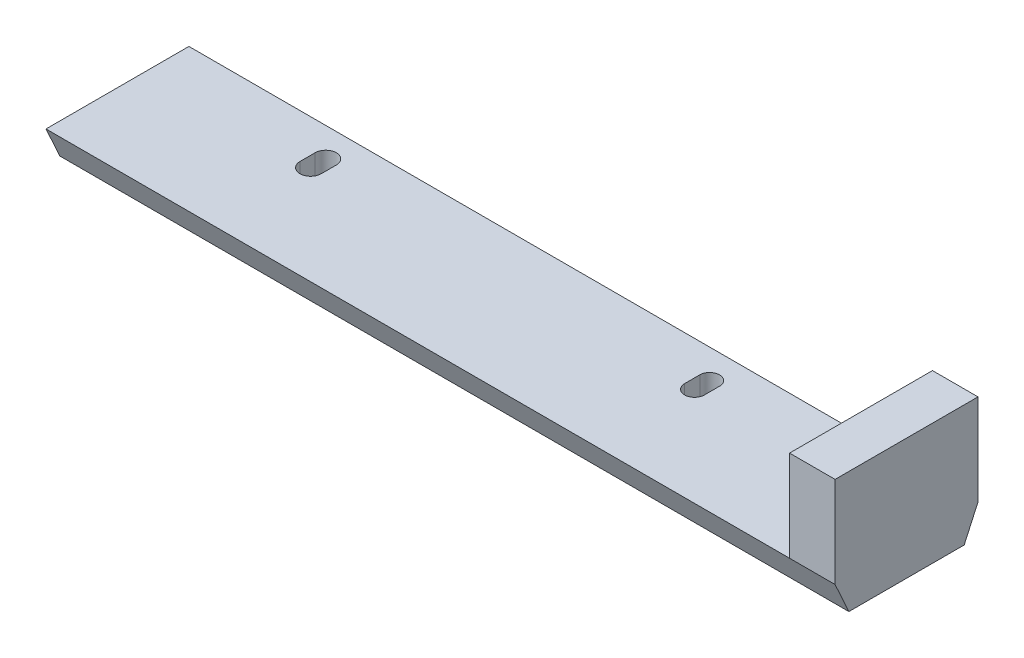
SolidWorks part; units mm, degrees
other "标注1"
sketch "草图3" plane through (-22.25, 4, -10) normal (-0.231, 0.6469, -0.7268) x (-0.9696, -0.2151, 0.1167)
other "标注2"
sketch "草图4" plane through (22.25, 8, -30) normal (0.0083, 0.0567, -0.9984) x (-0.9991, 0.0415, -0.0059)
ref_plane "前视基准面" through (0, 0, 0) normal (0, 0, 1) x (1, 0, 0)
ref_plane "上视基准面" through (0, 0, 0) normal (0, 1, 0) x (1, 0, 0)
ref_plane "右视基准面" through (0, 0, 0) normal (1, 0, 0) x (0, 0, -1)
other "Configuration Table"
sketch "草图1" plane through (0, 0, 0) normal (0, 1, 0) x (1, 0, 0)
  line L36 (0, -10) -> (52, -10)
  line L37 (0, -10) -> (0, 0)
  line L38 (0, 0) -> (52, 0)
  line L39 (52, -10) -> (52, 0)
  dimension "D1" = 10
  dimension "D2" = 52
extrude "凸台-拉伸1" add sketch "草图1" along normal blind 2
sketch "草图5" plane through (0, 2, 0) normal (0, 1, 0) x (1, 0, 0)
  line L2 (52, 0) -> (0, 0) construction
  line L3 (0, 0) -> (0, -10) construction
  circle A1 centre (36.2264, -2.7) radius 0.6
  circle A2 centre (10.9264, -2.7) radius 0.6
  dimension "D3" = 2.7
  dimension "D2" = 1.2
  dimension "D1" = 25.3
  dimension "D4" = 10.9264
extrude "切除-拉伸1" cut sketch "草图5" against normal through all
sketch "草图6" plane through (0, 2, 0) normal (0, 1, 0) x (1, 0, 0)
  line L0 (52, -10) -> (52, 0) construction
  line L1 (52, 0) -> (49, 0)
  line L2 (52, 0) -> (52, -10)
  line L3 (52, -10) -> (49, -10)
  line L4 (49, 0) -> (49, -10)
  line L5 (52, 0) -> (0, 0) construction
  line L6 (0, -10) -> (52, -10) construction
  dimension "D1" = 3
extrude "凸台-拉伸2" add sketch "草图6" along normal blind 6
sketch "草图7" plane through (0, 2, 0) normal (0, 1, 0) x (1, 0, 0)
  line L0 (10.9264, -2.2) -> (10.9264, -3.2) construction
  line L1 (11.6264, -2.2) -> (11.6264, -3.2)
  line L2 (10.2264, -2.2) -> (10.2264, -3.2)
  line L3 (36.2264, -2.2) -> (36.2264, -3.2) construction
  line L4 (36.8764, -2.2) -> (36.8764, -3.2)
  line L5 (35.5764, -2.2) -> (35.5764, -3.2)
  arc A0 (11.6264, -2.2) -> (10.2264, -2.2) centre (10.9264, -2.2) ccw
  arc A1 (10.2264, -3.2) -> (11.6264, -3.2) centre (10.9264, -3.2) ccw
  circle A3 centre (10.9264, -2.7) radius 0.6 construction
  arc A4 (36.8764, -2.2) -> (35.5764, -2.2) centre (36.2264, -2.2) ccw
  arc A5 (35.5764, -3.2) -> (36.8764, -3.2) centre (36.2264, -3.2) ccw
  circle A6 centre (36.2264, -2.7) radius 0.6 construction
  point P2 (10.9264, -2.7)
  point P7 (36.2264, -2.7)
  dimension "D1" = 1.4
  dimension "D2" = 1
  dimension "D3" = 1.3
extrude "切除-拉伸2" cut sketch "草图7" against normal through all
sketch "草图8" plane through (0, 2, 0) normal (0, 1, 0) x (1, 0, 0)
  line L0 (36.2264, -1.55) -> (36.2264, -3.85)
  arc A0 (36.8764, -2.2) -> (35.5764, -2.2) centre (36.2264, -2.2) ccw construction
  arc A1 (35.5764, -3.2) -> (36.8764, -3.2) centre (36.2264, -3.2) ccw construction
ref_plane "基准面1" through (36.2264, 0, 0) normal (1, 0, 0) x (0, 0, -1)
sketch "草图9" plane through (52, 0, 0) normal (1, 0, 0) x (0, 0, -1)
  line L0 (-0.2909, 2) -> (-1.2, 0)
  line L1 (0, 2) -> (-10, 2) construction
  line L2 (0, 0) -> (-10, 0) construction
  line L3 (-1.2, 0) -> (0, 0)
  line L4 (0, 0) -> (0, 8)
  line L7 (-9.7091, 2) -> (-8.8, 0)
  line L8 (-8.8, 0) -> (-10, 0)
  line L9 (-10, 2) -> (-10, 0) construction
  line L10 (-10, 0) -> (-10, 8)
  line L12 (-10, 8) -> (-9.7091, 8)
  line L13 (-10, 8) -> (0, 8) construction
  line L14 (-9.7091, 8) -> (-9.7091, 2)
  line L15 (-0.2909, 2) -> (-0.2909, 8)
  line L16 (-0.2909, 8) -> (0, 8)
  line L17 (0, 8) -> (0, 0) construction
  point P9 (0, 0)
  point P12 (0, 0)
  point P25 (0, 0)
  dimension "D1" = 1.2
  dimension "D2" = 0.2909
extrude "切除-拉伸3" cut sketch "草图9" against normal through all both
